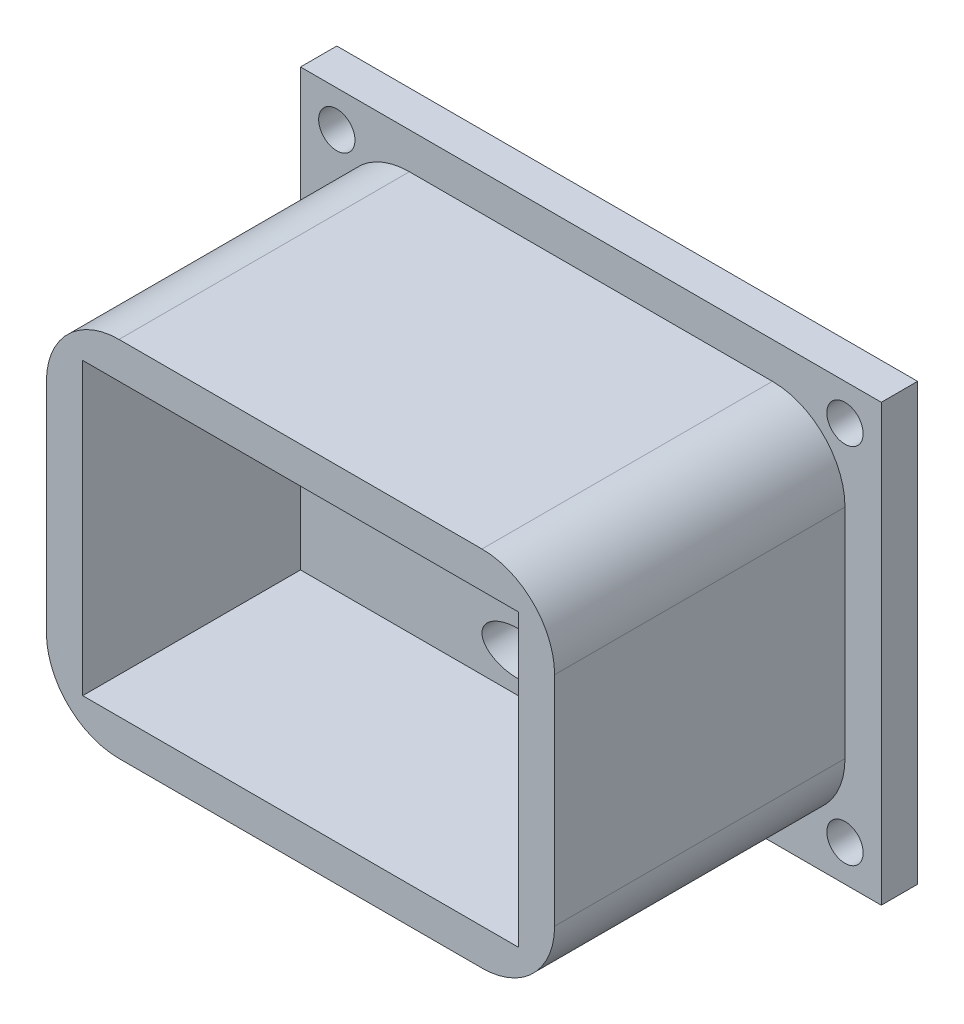
SolidWorks part; units mm, degrees
ref_plane "Front Plane" through (0, 0, 0) normal (0, 0, 1) x (1, 0, 0)
ref_plane "Top Plane" through (0, 0, 0) normal (0, 1, 0) x (1, 0, 0)
ref_plane "Right Plane" through (0, 0, 0) normal (1, 0, 0) x (0, 0, -1)
sketch "Sketch1" plane through (0, 0, 0) normal (0, 0, 1) x (1, 0, 0)
  line L1 (0, 0) -> (70, 0)
  line L2 (0, 0) -> (0, 50)
  line L3 (0, 50) -> (70, 50)
  line L4 (70, 0) -> (70, 50)
extrude "Boss-Extrude1" add sketch "Sketch1" along normal blind 40
sketch "Sketch2" plane through (0, 0, 40) normal (0, 0, 1) x (1, 0, 0)
  line L3 (5, 45) -> (65, 45)
  line L4 (65, 45) -> (65, 5)
  line L5 (65, 5) -> (5, 5)
  line L6 (5, 5) -> (5, 45)
extrude "Cut-Extrude1" cut sketch "Sketch2" against normal blind 30
sketch "Sketch4" plane through (0, 0, 0) normal (0, 0, -1) x (-1, 0, 0)
  line L1 (-75, 50) -> (-75, 55)
  line L2 (-75, 55) -> (5, 55)
  line L3 (5, 55) -> (5, -5)
  line L4 (5, -5) -> (-75, -5)
  line L5 (-75, -5) -> (-75, 50)
extrude "Boss-Extrude2" add sketch "Sketch4" along normal blind 5
fillet "Fillet1" radius 10 4 edges at (70, 0, 20) (0, 0, 20) (70, 50, 20) (0, 50, 20)
sketch "Sketch5" plane through (0, 0, 0) normal (0, 0, 1) x (1, 0, 0)
  circle A0 centre (0, 50) radius 2.5
  circle A1 centre (70, 50) radius 2.5
  circle A2 centre (70, 0) radius 2.5
  circle A3 centre (0, 0) radius 2.5
extrude "Cut-Extrude2" cut sketch "Sketch5" against normal blind 5
sketch "Sketch6" plane through (0, 0, 10) normal (0, 0, 1) x (1, 0, 0)
  ellipse E0 centre (35, 10) end of major axis (30, 10) minor radius 3
extrude "Cut-Extrude3" cut sketch "Sketch6" against normal blind 20
